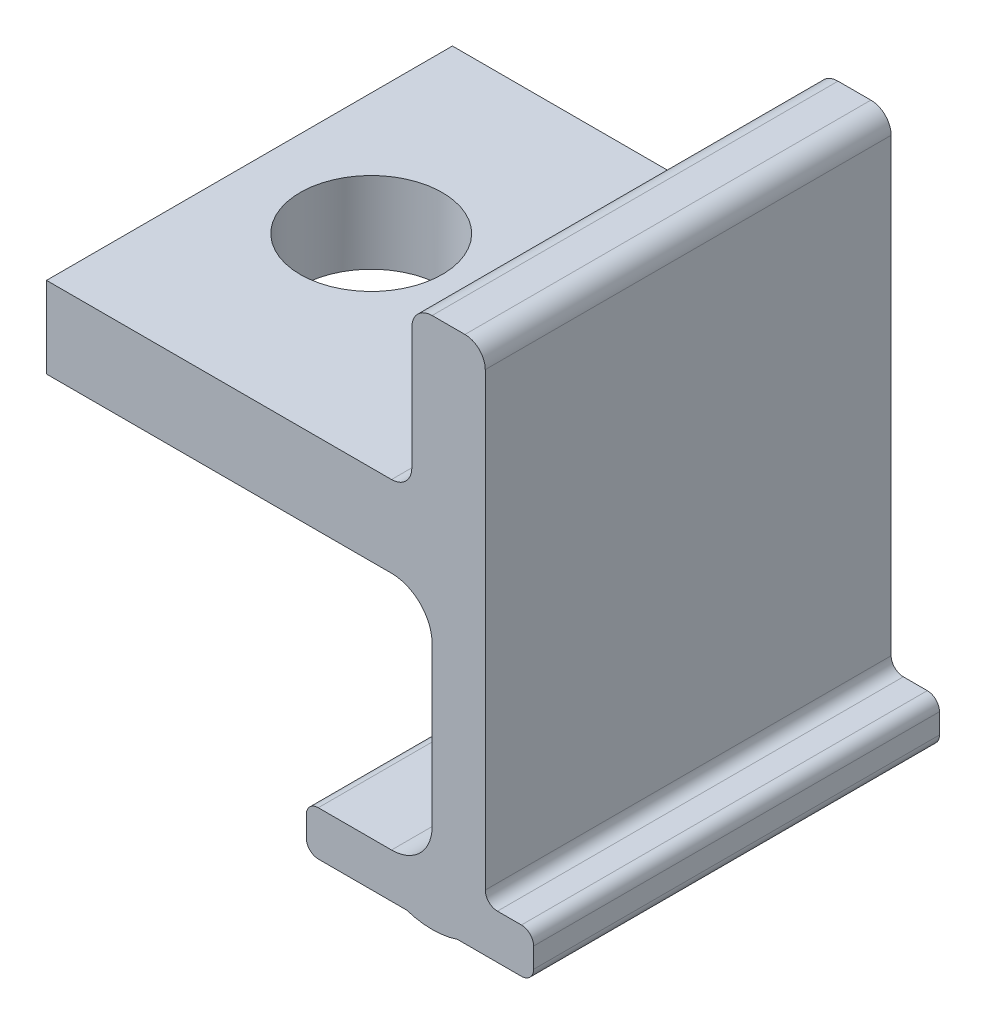
SolidWorks part; units mm, degrees
material "AISI 316"
ref_plane "Front Plane" through (0, 0, 0) normal (0, 0, 1) x (1, 0, 0)
ref_plane "Top Plane" through (0, 0, 0) normal (0, 1, 0) x (1, 0, 0)
ref_plane "Right Plane" through (0, 0, 0) normal (1, 0, 0) x (0, 0, -1)
sketch "Sketch1" plane through (0, 0, 0) normal (0, 0, 1) x (1, 0, 0)
  line L0 (0, 0) -> (8, 0)
  line L2 (8, -5.9) -> (12, -5.9) construction
  line L4 (11.7, -9) -> (10.1245, -9)
  line L6 (6.3, -2) -> (0, -2)
  line L7 (0, -2) -> (0, 0)
  line L9 (9.6, -9) -> (9.4, -9) construction
  line L10 (8.8755, -9) -> (6.3, -9)
  line L12 (10.3094, 4) -> (9.5, 4)
  line L13 (9, 3.5) -> (9, 0.5)
  line L15 (8, 0) -> (8.5, 0)
  line L16 (9.5, -9) -> (9.5, -7.1) construction
  line L17 (9.4, -9) -> (8.8755, -9) construction
  line L18 (10.1245, -9) -> (9.6, -9) construction
  line L19 (6.5, -2.2) -> (6.5, -7.6084)
  line L20 (6, -8.7) -> (6, -8.2)
  line L21 (12, -8.7) -> (12, -8.2042)
  line L22 (10.8094, 3.5) -> (10.8094, -7.6042)
  line L23 (11.1094, -7.9042) -> (11.7, -7.9042)
  line L24 (11.1094, -7.9042) -> (5.2529, -7.9042) construction
  arc A0 (9.6, -9) -> (9.5, -8.9) centre (9.5, -9) ccw construction
  arc A1 (9.4, -9) -> (9.6, -9) centre (9.5, -9) ccw construction
  arc A3 (10.8094, 3.5) -> (10.3094, 4) centre (10.3094, 3.5) ccw
  arc A4 (9.5, 4) -> (9, 3.5) centre (9.5, 3.5) ccw
  arc A5 (9, 0.5) -> (8.5, 0) centre (8.5, 0.5) cw
  arc A7 (6.5, -2.2) -> (6.3, -2) centre (6.3, -2.2) ccw
  arc A10 (8.8755, -9) -> (10.1245, -9) centre (9.5, -7.1) ccw
  arc A11 (7.9, -5.9) -> (8.8755, -9) centre (9.5, -7.1) ccw construction
  arc A12 (11.1, -5.9) -> (7.9, -5.9) centre (9.5, -7.1) ccw construction
  arc A13 (10.1245, -9) -> (11.1, -5.9) centre (9.5, -7.1) ccw construction
  arc A14 (9.5, -8.9) -> (9.4, -9) centre (9.5, -9) ccw construction
  arc A15 (12, -8.7) -> (11.7, -9) centre (11.7, -8.7) cw
  arc A16 (6.5, -7.6084) -> (6.25, -7.9042) centre (6.2, -7.6084) cw
  arc A17 (6.25, -7.9042) -> (6, -8.2) centre (6.3, -8.2) ccw
  arc A18 (6.3, -9) -> (6, -8.7) centre (6.3, -8.7) cw
  arc A19 (12, -8.2042) -> (11.7, -7.9042) centre (11.7, -8.2042) ccw
  arc A20 (10.8094, -7.6042) -> (11.1094, -7.9042) centre (11.1094, -7.6042) ccw
  point P21 (10.5, 4)
  point P24 (9, 4)
  point P29 (8, 0)
  point P42 (9.5, -9.1)
  point P45 (12, -8.9)
  dimension "D7" = 0.2
  dimension "D10" = 4
  dimension "D11" = 0.2
  dimension "D12" = 0.5
  dimension "D15" = 2
  dimension "D16" = 0.3
  dimension "D17" = 0.3
  dimension "D18" = 0.3
  dimension "D19" = 0.3
  dimension "D21" = 0.3
  dimension "D1" = 8
  dimension "D2" = 6.5
  dimension "D3" = 9
  dimension "D4" = 7
  dimension "D5" = 3
  dimension "D6" = 6
  dimension "D8" = 2
  dimension "D9" = 1.5
  dimension "D13" = 3.5
  dimension "D14" = 0.1
  dimension "D20" = 0.5
extrude "Boss-Extrude1" add sketch "Sketch1" along normal blind 10
fillet "Fillet1" [suppressed] radius 0.5
hole_wizard "M3 Clearance Hole1" positions "Sketch2" profile "Sketch3" hole size "M3" standard "ISO" end condition through all
sketch "Sketch2" plane through (0, 0, 0) normal (0, 1, 0) x (1, 0, 0)
  point P0 (3, -5)
sketch "Sketch3" plane through (3, 0, 5) normal (1, 0, 0) x (0, 0, 1)
  line L0 (0, 0) -> (0, 9.1)
  line L1 (0, 9.1) -> (1.75, 9.1)
  line L2 (1.75, 9.1) -> (1.75, 0)
  line L5 (1.75, 0) -> (0, 0)
  line L11 (0, -6.35) -> (0, 107.95) construction
  dimension "Thru Hole Dia." = 3.5
  dimension "Thru Hole Depth" = 9.1
sketch "Sketch4" plane through (0, 0, 10) normal (0, 0, 1) x (1, 0, 0)
  line L1 (5.7641, -2) -> (8.5, -2)
  line L2 (5.7641, -2) -> (5.7641, -7.9042)
  line L3 (5.7641, -7.9042) -> (8.5, -7.9042)
  line L4 (9.5, -3) -> (9.5, -6.9042)
  line L5 (6.5, -2.2) -> (6.5, -7.6084) construction
  line L6 (8.5, 0) -> (0, 0) construction
  arc A0 (8.5, -2) -> (9.5, -3) centre (8.5, -3) cw
  arc A1 (8.5, -7.9042) -> (9.5, -6.9042) centre (8.5, -6.9042) ccw
  dimension "D2" = 1
  dimension "D1" = 3
  dimension "D3" = 2
extrude "Cut-Extrude1" cut sketch "Sketch4" against normal blind 10
sketch "Sketch5" plane through (0, -9, 0) normal (0, -1, 0) x (1, 0, 0)
  line L1 (8.2, 11) -> (8.2, -1) construction
  line L2 (0, 10) -> (0, 0) construction
  line L3 (6, 8.8) -> (6, 1.2)
  line L4 (6, 10) -> (6, 0) construction
  line L5 (6.3561, 10) -> (6.3561, 0) construction
  line L8 (6.3, 10) -> (8.8755, 10) construction
  circle A1 centre (8.2, 8.8) radius 2.2
  circle A2 centre (8.2, 1.2) radius 2.2
  point P2 (8.2, 5)
  point P5 (0, 5)
  dimension "D1" = 12
  dimension "D3" = 4.4
  dimension "D4" = 4.4
  dimension "D2" = 0
  dimension "D5" = 0
  dimension "D6" = 0.3561
sketch "Sketch6" plane through (0, 0, 10) normal (0, 0, 1) x (1, 0, 0)
  line L1 (6.25, -7.9042) -> (8.5, -7.9042) construction
  line L2 (6.4, -8.2) -> (6.4, -8.7)
  line L3 (6.4, -8.2) -> (6.4, -8.7)
  line L4 (6.3, -9) -> (8.8755, -9) construction
  line L5 (6, -8.2) -> (6, -8.7) construction
  line L6 (6.3, -9) -> (6.7, -9)
  line L7 (6, -8.2) -> (6, -8.7)
  line L8 (6.25, -7.9042) -> (6.6958, -7.9042)
  arc A0 (6.6958, -7.9042) -> (6.4, -8.2) centre (6.6958, -8.2) ccw
  arc A1 (6.4, -8.7) -> (6.7, -9) centre (6.7, -8.7) ccw
  arc A2 (6, -8.7) -> (6.3, -9) centre (6.3, -8.7) ccw construction
  arc A3 (6.25, -7.9042) -> (6, -8.2) centre (6.3, -8.2) ccw construction
  arc A4 (6, -8.7) -> (6.3, -9) centre (6.3, -8.7) ccw
  arc A5 (6.25, -7.9042) -> (6, -8.2) centre (6.3, -8.2) ccw
  dimension "D1" = 0.4
extrude "Cut-Extrude2" cut sketch "Sketch6" against normal blind 10
